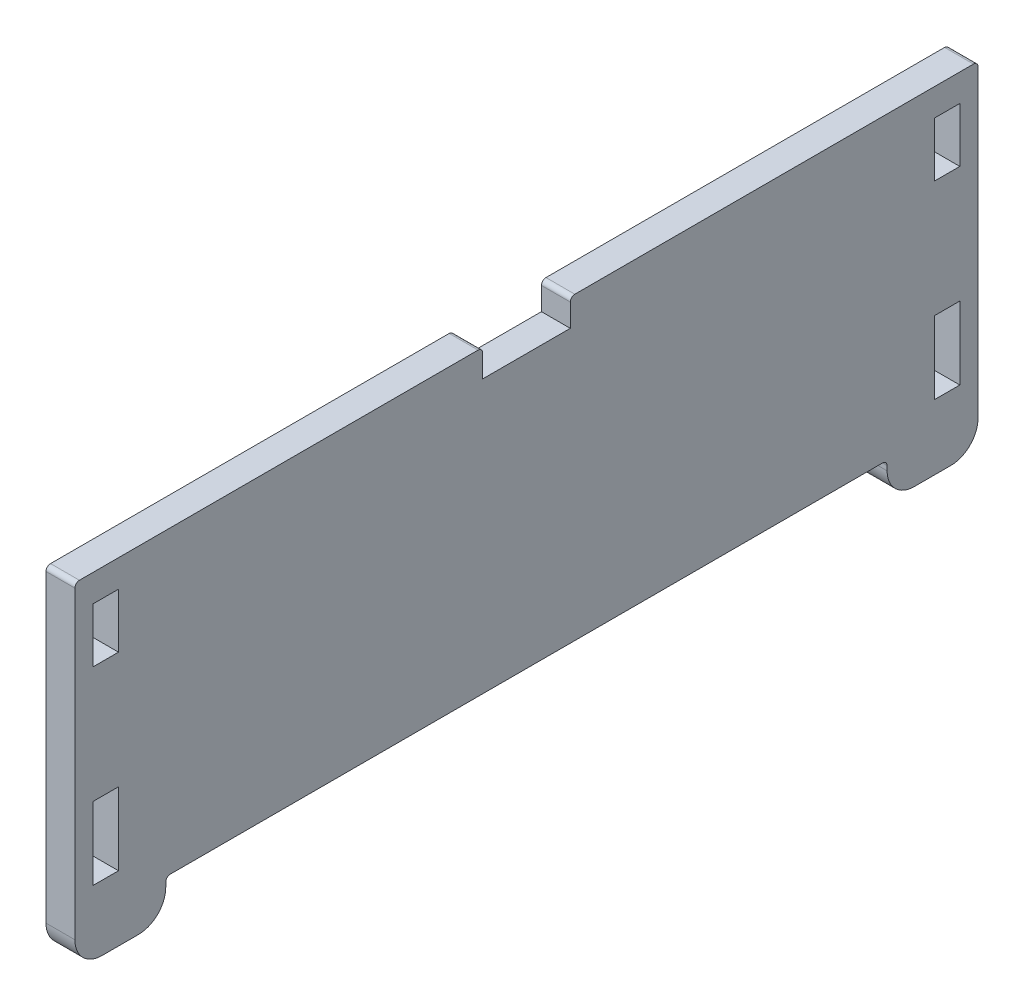
SolidWorks part; units mm, degrees
ref_plane "Front Plane" through (0, 0, 0) normal (0, 0, 1) x (1, 0, 0)
ref_plane "Top Plane" through (0, 0, 0) normal (0, 1, 0) x (1, 0, 0)
ref_plane "Right Plane" through (0, 0, 0) normal (1, 0, 0) x (0, 0, -1)
sketch "Sketch1" plane through (0, 0, 0) normal (1, 0, 0) x (0, 0, -1)
  line L1 (-49.675, -18.5) -> (49.675, -18.5)
  line L2 (-49.675, -18.5) -> (-49.675, 18.5)
  line L3 (-49.675, 18.5) -> (49.675, 18.5)
  line L4 (49.675, -18.5) -> (49.675, 18.5)
  line L5 (-49.675, -18.5) -> (49.675, 18.5) construction
  line L6 (-49.675, 18.5) -> (49.675, -18.5) construction
  point P0 (0, 0)
  dimension "D1" = 99.35
  dimension "D2" = 37
extrude "Boss-Extrude1" add sketch "Sketch1" along normal blind 3.175
sketch "Sketch2" plane through (3.175, 0, 0) normal (1, 0, 0) x (0, 0, -1)
  line L0 (49.675, 18.5) -> (-49.675, 18.5) construction
  line L1 (-47.675, 15.5) -> (-44.875, 15.5)
  line L2 (-47.675, 15.5) -> (-47.675, 9.5)
  line L3 (-47.675, 9.5) -> (-44.875, 9.5)
  line L4 (-44.875, 15.5) -> (-44.875, 9.5)
  line L5 (-49.675, 18.5) -> (-49.675, -18.5) construction
  line L6 (49.675, -18.5) -> (49.675, 18.5) construction
  line L7 (44.875, 15.5) -> (47.675, 15.5)
  line L8 (44.875, 15.5) -> (44.875, 9.5)
  line L9 (44.875, 9.5) -> (47.675, 9.5)
  line L10 (47.675, 15.5) -> (47.675, 9.5)
  line L12 (-47.675, -3.325) -> (-44.875, -3.325)
  line L13 (-47.675, -3.325) -> (-47.675, -11.325)
  line L14 (-47.675, -11.325) -> (-44.875, -11.325)
  line L15 (-44.875, -3.325) -> (-44.875, -11.325)
  line L16 (-49.675, -18.5) -> (49.675, -18.5) construction
  line L17 (44.875, -3.325) -> (47.675, -3.325)
  line L18 (44.875, -3.325) -> (44.875, -11.325)
  line L19 (44.875, -11.325) -> (47.675, -11.325)
  line L20 (47.675, -3.325) -> (47.675, -11.325)
  dimension "D1" = 2.8
  dimension "D2" = 6
  dimension "D3" = 3
  dimension "D4" = 2
  dimension "D5" = 2.8
  dimension "D6" = 3
  dimension "D7" = 2
  dimension "D8" = 6
  dimension "D9" = 2.8
  dimension "D10" = 8
  dimension "D11" = 2
  dimension "D12" = 7.175
  dimension "D13" = 8
  dimension "D14" = 2.8
  dimension "D15" = 2
  dimension "D16" = 7.175
extrude "Cut-Extrude1" cut sketch "Sketch2" against normal through all
sketch "Sketch3" plane through (3.175, 0, 0) normal (1, 0, 0) x (0, 0, -1)
  line L0 (-49.675, -18.5) -> (49.675, -18.5) construction
  line L1 (-39.675, -18.5) -> (39.675, -18.5)
  line L2 (-39.675, -18.5) -> (-39.675, -14.5)
  line L3 (-39.675, -14.5) -> (39.675, -14.5)
  line L4 (39.675, -18.5) -> (39.675, -14.5)
  line L5 (49.675, 18.5) -> (-49.675, 18.5) construction
  line L6 (-49.675, 18.5) -> (-49.675, -18.5) construction
  line L7 (49.675, -18.5) -> (49.675, 18.5) construction
  dimension "D1" = 33
  dimension "D2" = 10
  dimension "D3" = 10
extrude "Cut-Extrude2" cut sketch "Sketch3" against normal through all
fillet "Fillet1" radius 3 4 edges at (1.5875, -18.5, -49.675) (1.5875, -18.5, -39.675) (1.5875, -18.5, 39.675) (1.5875, -18.5, 49.675)
fillet "Fillet2" radius 0.5 4 edges at (1.5875, 18.5, -49.675) (1.5875, 18.5, 49.675) (1.5875, -14.5, -39.675) (1.5875, -14.5, 39.675)
sketch "Sketch4" plane through (3.175, 0, 0) normal (1, 0, 0) x (0, 0, -1)
  line L0 (49.175, 18.5) -> (-49.175, 18.5) construction
  line L1 (-4.825, 18.5) -> (4.825, 18.5)
  line L2 (-4.825, 18.5) -> (-4.825, 15.5)
  line L3 (-4.825, 15.5) -> (4.825, 15.5)
  line L4 (4.825, 18.5) -> (4.825, 15.5)
  dimension "D1" = 9.65
  dimension "D2" = 4.825
  dimension "D3" = 3
extrude "Cut-Extrude3" cut sketch "Sketch4" against normal through all
fillet "Fillet3" radius 0.5 2 edges at (1.5875, 18.5, -4.825) (1.5875, 18.5, 4.825)
